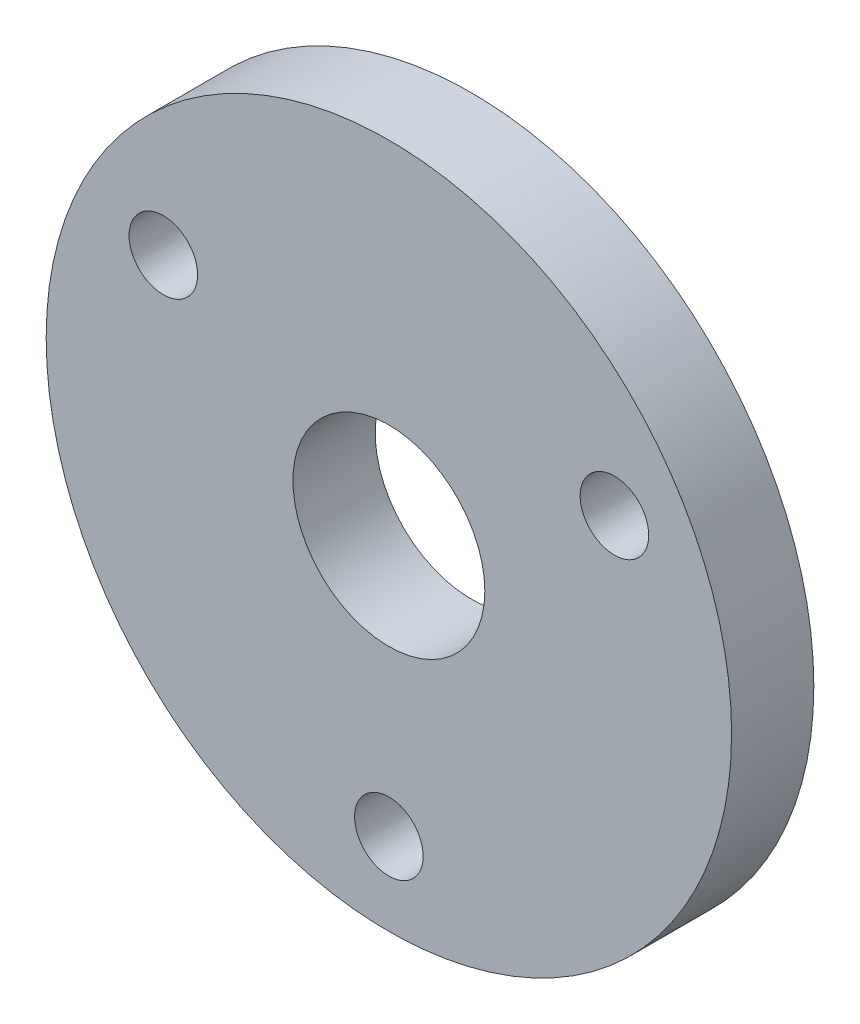
SolidWorks part; units mm, degrees
ref_plane "Front Plane" through (0, 0, 0) normal (0, 0, 1) x (1, 0, 0)
ref_plane "Top Plane" through (0, 0, 0) normal (0, 1, 0) x (1, 0, 0)
ref_plane "Right Plane" through (0, 0, 0) normal (1, 0, 0) x (0, 0, -1)
sketch "Sketch1" plane through (0, 0, 0) normal (0, 0, 1) x (1, 0, 0)
  circle A0 centre (0, 0) radius 25
  circle A1 centre (0, 0) radius 7
  circle A2 centre (0, 0) radius 19 construction
  circle A3 centre (0, -19) radius 2.5
  circle A4 centre (-16.4545, 9.5) radius 2.5
  circle A5 centre (16.4545, 9.5) radius 2.5
  point P13 (0, 0)
  dimension "D1" = 50
  dimension "D2" = 14
  dimension "D3" = 38
  dimension "D4" = 5
  dimension "D5" = 3
extrude "Boss-Extrude1" add sketch "Sketch1" along normal blind 6
